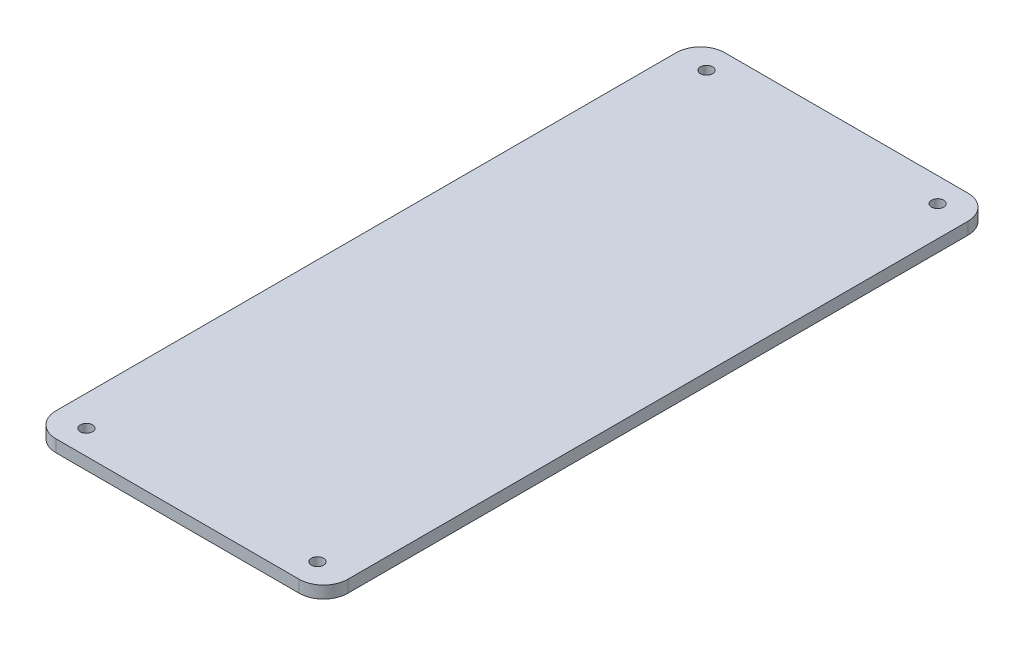
SolidWorks part; units mm, degrees
ref_plane "Front Plane" through (0, 0, 0) normal (0, 0, 1) x (1, 0, 0)
ref_plane "Top Plane" through (0, 0, 0) normal (0, 1, 0) x (1, 0, 0)
ref_plane "Right Plane" through (0, 0, 0) normal (1, 0, 0) x (0, 0, -1)
sketch "Sketch1" plane through (0, 0, 0) normal (0, 1, 0) x (1, 0, 0)
  line L0 (-28.5, 76.5) -> (-28.5, -76.5) construction
  line L1 (-30, -82.5) -> (30, -82.5)
  line L2 (-36, -76.5) -> (-36, 76.5)
  line L3 (-30, 82.5) -> (30, 82.5)
  line L4 (36, -76.5) -> (36, 76.5)
  line L5 (-36, -82.5) -> (36, 82.5) construction
  line L6 (-36, 82.5) -> (36, -82.5) construction
  line L7 (-28.5, -76.5) -> (28.5, -76.5) construction
  line L8 (28.5, -76.5) -> (28.5, 76.5) construction
  line L9 (28.5, 76.5) -> (-28.5, 76.5) construction
  line L10 (-28.5, -28.5) -> (28.5, -28.5) construction
  line L11 (-28.5, 28.5) -> (28.5, 28.5) construction
  arc A0 (30, 82.5) -> (36, 76.5) centre (30, 76.5) cw
  arc A1 (36, -76.5) -> (30, -82.5) centre (30, -76.5) cw
  arc A2 (-30, -82.5) -> (-36, -76.5) centre (-30, -76.5) cw
  arc A3 (-36, 76.5) -> (-30, 82.5) centre (-30, 76.5) cw
  circle A4 centre (28.5, -76.5) radius 1.5
  circle A5 centre (-28.5, -76.5) radius 1.5
  circle A6 centre (28.5, 76.5) radius 1.5
  circle A7 centre (-28.5, 76.5) radius 1.5
  circle A8 centre (-28.5, -28.5) radius 1.5 construction
  circle A9 centre (28.5, -28.5) radius 1.5 construction
  circle A10 centre (28.5, 28.5) radius 1.5 construction
  circle A11 centre (-28.5, 28.5) radius 1.5 construction
  point P0 (0, 0)
  dimension "D3" = 3
  dimension "D4" = 6
  dimension "D5" = 7.5
  dimension "D6" = 57
  dimension "D7" = 153
  dimension "D8" = 6
  dimension "D10" = 48
  dimension "D1" = 72
  dimension "D2" = 165
  dimension "D9" = 48
extrude "Boss-Extrude1" add sketch "Sketch1" along normal blind 3
